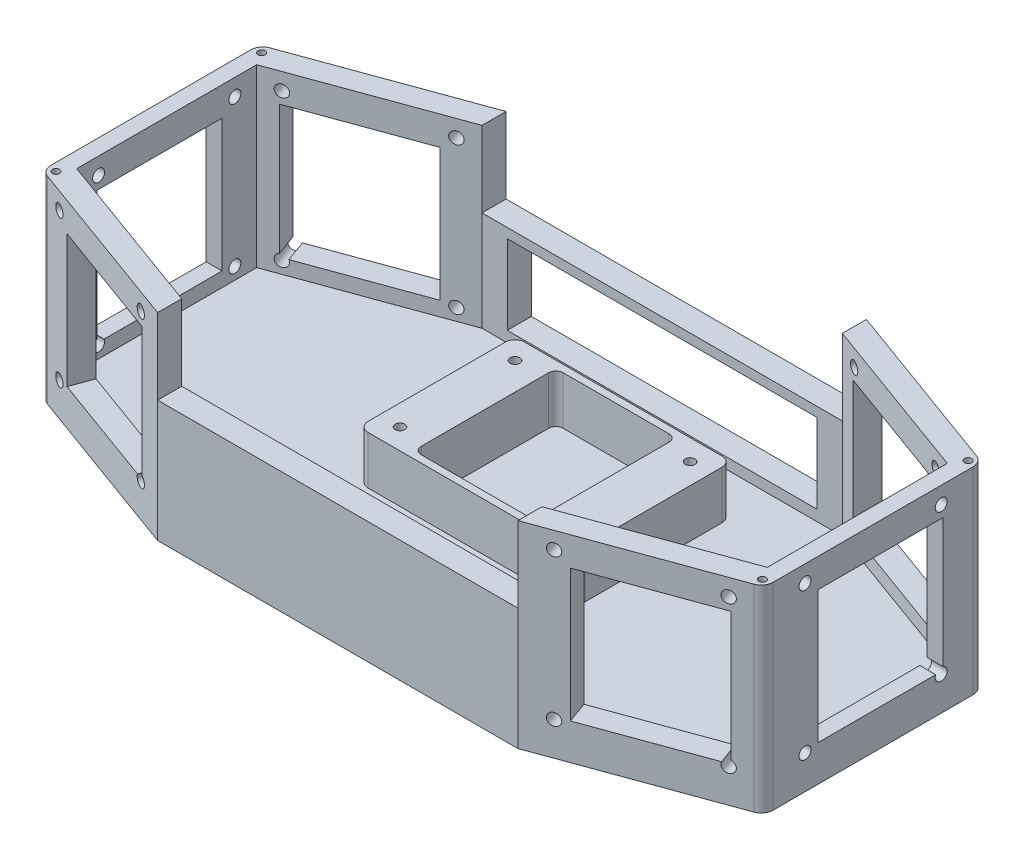
SolidWorks part; units mm, degrees
material "ABS"
ref_plane "Front Plane" through (0, 0, 0) normal (0, 0, 1) x (1, 0, 0)
ref_plane "Top Plane" through (0, 0, 0) normal (0, 1, 0) x (1, 0, 0)
ref_plane "Right Plane" through (0, 0, 0) normal (1, 0, 0) x (0, 0, -1)
sketch "Sketch1" plane through (0, 0, 0) normal (0, 1, 0) x (1, 0, 0)
  line L0 (-150, 0) -> (150, 0) construction
  line L1 (-150, 45) -> (-150, -45)
  line L2 (140.0883, -41.1583) -> (79.948, -63.0476) construction
  line L3 (-140.0883, 41.1583) -> (-142.4825, 47.7362) construction
  line L4 (-140.0883, 41.1583) -> (-79.948, 63.0476) construction
  line L5 (-150, 45) -> (-74.8246, 72.3616)
  line L6 (-79.948, 63.0476) -> (-82.3421, 69.6255) construction
  line L7 (-143, 32) -> (-143, -32) construction
  line L8 (-140.0883, -41.1583) -> (-142.4825, -47.7362) construction
  line L9 (-79.948, -63.0476) -> (-82.3421, -69.6255) construction
  line L10 (-140.0883, -41.1583) -> (-79.948, -63.0476) construction
  line L11 (-150, -45) -> (-74.8246, -72.3616)
  line L12 (0, 74.8501) -> (0, -82.9126) construction
  line L13 (79.948, -63.0476) -> (82.3421, -69.6255) construction
  line L14 (140.0883, -41.1583) -> (142.4825, -47.7362) construction
  line L15 (143, 32) -> (143, -32) construction
  line L16 (79.948, 63.0476) -> (82.3421, 69.6255) construction
  line L17 (140.0883, 41.1583) -> (79.948, 63.0476) construction
  line L18 (140.0883, 41.1583) -> (142.4825, 47.7362) construction
  line L19 (150, -45) -> (74.8246, -72.3616)
  line L20 (150, 45) -> (74.8246, 72.3616)
  line L21 (150, 45) -> (150, -45)
  line L22 (-74.8246, 72.3616) -> (74.8246, 72.3616)
  line L23 (-74.8246, -72.3616) -> (74.8246, -72.3616)
  point P0 (0, 0)
  point P3 (-150, 0)
  point P10 (-143, 0)
  point P13 (0, 0)
  point P37 (143, 0)
  dimension "D1" = 7
  dimension "D2" = 90
  dimension "D3" = 64
  dimension "D4" = 300
  dimension "D5" = 7
  dimension "D6" = 8
  dimension "D7" = 80
  dimension "D8" = 110
extrude "Boss-Extrude1" add sketch "Sketch1" along normal blind 8
sketch "Sketch2" plane through (0, 8, 0) normal (0, 1, 0) x (1, 0, 0)
  line L0 (0, 72.3616) -> (0, -72.3616) construction
  line L1 (74.8246, 72.3616) -> (-74.8246, 72.3616) construction
  line L2 (-74.8246, -72.3616) -> (74.8246, -72.3616) construction
  line L3 (-74.8246, -72.3616) -> (-74.8246, -62.3616) construction
  line L4 (-74.8246, -62.3616) -> (-64.3246, -62.3616) construction
  line L5 (-64.3246, -62.3616) -> (-64.3246, -72.3616) construction
  line L6 (-64.3246, -72.3616) -> (-74.8246, -72.3616) construction
  line L7 (64.3246, -72.3616) -> (74.8246, -72.3616) construction
  line L8 (64.3246, -62.3616) -> (64.3246, -72.3616) construction
  line L9 (74.8246, -62.3616) -> (64.3246, -62.3616) construction
  line L10 (74.8246, -72.3616) -> (74.8246, -62.3616) construction
  line L11 (-150, 0) -> (150, 0) construction
  line L12 (-150, 45) -> (-150, -45) construction
  line L13 (150, -45) -> (150, 45) construction
  line L14 (74.8246, 72.3616) -> (74.8246, 62.3616)
  line L15 (74.8246, 62.3616) -> (64.3246, 62.3616)
  line L16 (64.3246, 62.3616) -> (64.3246, 72.3616)
  line L17 (64.3246, 72.3616) -> (74.8246, 72.3616)
  line L18 (-64.3246, 72.3616) -> (-74.8246, 72.3616)
  line L19 (-64.3246, 62.3616) -> (-64.3246, 72.3616)
  line L20 (-74.8246, 62.3616) -> (-64.3246, 62.3616)
  line L21 (-74.8246, 72.3616) -> (-74.8246, 62.3616)
  dimension "D1" = 10.5
  dimension "D2" = 10
extrude "Boss-Extrude2" add sketch "Sketch2" along normal blind 37.5
sketch "Sketch4" plane through (0, 8, 0) normal (0, 1, 0) x (1, 0, 0)
  line L1 (-64.3246, 72.3616) -> (64.3246, 72.3616)
  line L2 (-64.3246, 72.3616) -> (-64.3246, 62.3616)
  line L3 (-64.3246, 62.3616) -> (64.3246, 62.3616)
  line L4 (64.3246, 72.3616) -> (64.3246, 62.3616)
extrude "Boss-Extrude4" add sketch "Sketch4" along normal blind 4.5
sketch "Sketch5" plane through (0, 8, 0) normal (0, 1, 0) x (1, 0, 0)
  line L0 (-74.8246, 62.3616) -> (-87.0406, 57.9153)
  line L1 (-74.8246, 72.3616) -> (-150, 45) construction
  line L2 (-74.8246, 72.3616) -> (-74.8246, 62.3616)
  line L3 (-74.8246, 72.3616) -> (-150, 45)
  line L4 (-87.0406, 57.9153) -> (-140.6031, 38.4202)
  line L5 (-150, 45) -> (-140.6031, 38.4202) construction
  line L6 (-74.8246, -72.3616) -> (-74.8246, -62.3616)
  line L7 (-140.6031, 38.4202) -> (-143.4222, 37.3941)
  line L8 (-150, 45) -> (-143.4222, 37.3941) construction
  line L9 (-150, 0) -> (-74.8246, 0) construction
  line L10 (-150, 45) -> (-150, -45) construction
  line L11 (-79.6003, 0) -> (86.9407, 0) construction
  line L12 (-124.0599, 0) -> (-121.8599, 0) construction
  line L13 (-74.8246, -62.3616) -> (-87.0406, -57.9153)
  line L14 (-140.6031, -38.4202) -> (-143.4222, -37.3941)
  line L15 (-87.0406, -57.9153) -> (-140.6031, -38.4202)
  line L16 (-150, -45) -> (-143.4222, -37.3941) construction
  line L17 (-74.8246, -72.3616) -> (-150, -45)
  line L18 (-143.4222, 37.3941) -> (-143.4222, -37.3941)
  line L19 (-150, 45) -> (-150, -45)
  line L20 (0, 72.1209) -> (0, -72.3616) construction
  line L21 (-74.8246, -72.3616) -> (74.8246, -72.3616) construction
  line L22 (150, -45) -> (143.4222, -37.3941) construction
  line L23 (150, 0) -> (74.8246, 0) construction
  line L24 (150, 45) -> (143.4222, 37.3941) construction
  line L25 (150, 45) -> (140.6031, 38.4202) construction
  line L26 (150, 45) -> (150, -45)
  line L27 (143.4222, 37.3941) -> (143.4222, -37.3941)
  line L28 (74.8246, -72.3616) -> (150, -45)
  line L29 (87.0406, -57.9153) -> (140.6031, -38.4202)
  line L30 (140.6031, -38.4202) -> (143.4222, -37.3941)
  line L31 (74.8246, -62.3616) -> (87.0406, -57.9153)
  line L32 (140.6031, 38.4202) -> (143.4222, 37.3941)
  line L33 (74.8246, -72.3616) -> (74.8246, -62.3616)
  line L34 (87.0406, 57.9153) -> (140.6031, 38.4202)
  line L35 (74.8246, 72.3616) -> (150, 45)
  line L36 (74.8246, 72.3616) -> (74.8246, 62.3616)
  line L37 (74.8246, 62.3616) -> (87.0406, 57.9153)
  dimension "D1" = 13
  dimension "D2" = 55
  dimension "D3" = 3
extrude "Boss-Extrude5" add sketch "Sketch5" along normal blind 10
sketch "Sketch6" plane through (0, 45.5, 0) normal (0, 1, 0) x (1, 0, 0)
  line L1 (74.8246, 72.3616) -> (-74.8246, 72.3616)
  line L2 (74.8246, 72.3616) -> (74.8246, 62.3616)
  line L3 (74.8246, 62.3616) -> (-74.8246, 62.3616)
  line L4 (-74.8246, 72.3616) -> (-74.8246, 62.3616)
extrude "Boss-Extrude6" add sketch "Sketch6" along normal blind 4
sketch "Sketch7" plane through (32.0094, 0, -87.9451) normal (0.342, 0, -0.9397) x (-0.9397, 0, -0.342)
  line L0 (-85.563, 18) -> (-85.563, 0) construction
  line L1 (-125.563, 18) -> (-45.563, 18) construction
  line L2 (-125.563, 0) -> (-45.563, 0) construction
  line L3 (-113.853, 13) -> (-85.563, 13) construction
  circle A0 centre (-113.853, 13) radius 2.5
  circle A1 centre (-57.273, 13) radius 2.5
  dimension "D1" = 56.58
  dimension "D2" = 5
  dimension "D3" = 5
extrude "Cut-Extrude1" cut sketch "Sketch7" against normal up to next
ref_plane "Plane1" through (0, 0, 0) normal (1, 0, 0) x (0, 0, -1)
mirror "Mirror1" about plane through (0, 0, 0) normal (1, 0, 0) of "Cut-Extrude1"
ref_plane "Plane2" through (0, 0, 0) normal (0, 0, -1) x (-1, 0, 0)
mirror "Mirror2" about plane through (0, 0, 0) normal (0, 0, -1) of "Cut-Extrude1", "Mirror1"
sketch "Sketch8" plane through (150, 0, 0) normal (1, 0, 0) x (0, 0, -1)
  line L0 (0, 18) -> (0, 0) construction
  line L1 (-45, 18) -> (45, 18) construction
  line L2 (-28.29, 13) -> (28.29, 13) construction
  line L3 (0, -27.775) -> (0, 27.775) construction
  circle A0 centre (-28.29, 13) radius 2.5
  circle A1 centre (28.29, 13) radius 2.5
  point P8 (0, 13)
  dimension "D1" = 56.58
  dimension "D3" = 5
  dimension "D2" = 5
extrude "Cut-Extrude2" cut sketch "Sketch8" against normal up to next
mirror "Mirror3" about plane through (0, 0, 0) normal (1, 0, 0) of "Cut-Extrude2"
sketch "Sketch9" plane through (0, 18, 0) normal (0, 1, 0) x (1, 0, 0)
  line L0 (143.4222, 23) -> (150, 23)
  line L1 (143.4222, 37.3941) -> (143.4222, -37.3941) construction
  line L2 (150, -45) -> (150, 45) construction
  line L3 (150, 23) -> (150, 45)
  line L4 (150, 45) -> (134.0252, 50.8143)
  line L5 (150, 45) -> (74.8246, 72.3616) construction
  line L6 (134.0252, 50.8143) -> (130.8113, 41.9841)
  line L7 (74.8246, 62.3616) -> (143.4222, 37.3941) construction
  line L8 (130.8113, 41.9841) -> (143.4222, 37.3941)
  line L9 (143.4222, 37.3941) -> (143.4222, 23)
  line L12 (74.8246, 72.3616) -> (90.7994, 66.5473)
  line L13 (90.7994, 66.5473) -> (87.5854, 57.717)
  line L14 (87.5854, 57.717) -> (74.8246, 62.3616)
  line L15 (74.8246, 72.3616) -> (74.8246, 62.3616) construction
  line L16 (74.8246, 62.3616) -> (74.8246, 72.3616)
  line L17 (0, -70.7131) -> (0, 92.4677) construction
  line L18 (-74.8246, 62.3616) -> (-74.8246, 72.3616)
  line L19 (-87.5854, 57.717) -> (-74.8246, 62.3616)
  line L20 (-90.7994, 66.5473) -> (-87.5854, 57.717)
  line L21 (-74.8246, 72.3616) -> (-90.7994, 66.5473)
  line L22 (-143.4222, 37.3941) -> (-143.4222, 23)
  line L23 (-130.8113, 41.9841) -> (-143.4222, 37.3941)
  line L24 (-134.0252, 50.8143) -> (-130.8113, 41.9841)
  line L25 (-150, 45) -> (-134.0252, 50.8143)
  line L26 (-150, 23) -> (-150, 45)
  line L27 (-143.4222, 23) -> (-150, 23)
  line L28 (150, 0) -> (-150, 0) construction
  line L29 (-150, 45) -> (-150, -45) construction
  line L30 (143.4222, -37.3941) -> (143.4222, -23)
  line L31 (130.8113, -41.9841) -> (143.4222, -37.3941)
  line L32 (134.0252, -50.8143) -> (130.8113, -41.9841)
  line L33 (150, -45) -> (134.0252, -50.8143)
  line L34 (150, -23) -> (150, -45)
  line L35 (143.4222, -23) -> (150, -23)
  line L36 (-143.4222, -23) -> (-150, -23)
  line L37 (-150, -23) -> (-150, -45)
  line L38 (-150, -45) -> (-134.0252, -50.8143)
  line L39 (-134.0252, -50.8143) -> (-130.8113, -41.9841)
  line L40 (-130.8113, -41.9841) -> (-143.4222, -37.3941)
  line L41 (-143.4222, -37.3941) -> (-143.4222, -23)
  line L42 (-74.8246, -72.3616) -> (-90.7994, -66.5473)
  line L43 (-90.7994, -66.5473) -> (-87.5854, -57.717)
  line L44 (-87.5854, -57.717) -> (-74.8246, -62.3616)
  line L45 (-74.8246, -62.3616) -> (-74.8246, -72.3616)
  line L46 (74.8246, -62.3616) -> (74.8246, -72.3616)
  line L47 (87.5854, -57.717) -> (74.8246, -62.3616)
  line L48 (90.7994, -66.5473) -> (87.5854, -57.717)
  line L49 (74.8246, -72.3616) -> (90.7994, -66.5473)
  dimension "D1" = 22
  dimension "D2" = 17
  dimension "D3" = 17
extrude "Boss-Extrude8" add sketch "Sketch9" along normal blind 63
sketch "Sketch10" plane through (32.0094, 0, -87.9451) normal (0.342, 0, -0.9397) x (-0.9397, 0, -0.342)
  line L0 (-85.563, 0) -> (-85.563, 86.9159) construction
  line L1 (-125.563, 0) -> (-45.563, 0) construction
  line L2 (-113.853, 13) -> (-113.853, 74) construction
  circle A0 centre (-113.853, 74) radius 2.5
  circle A1 centre (-113.853, 13) radius 2.5 construction
  circle A2 centre (-57.273, 74) radius 2.5
  dimension "D1" = 61
extrude "Cut-Extrude3" cut sketch "Sketch10" against normal up to next
mirror "Mirror4" about plane through (0, 0, 0) normal (1, 0, 0) of "Cut-Extrude3"
mirror "Mirror5" about plane through (0, 0, 0) normal (0, 0, -1) of "Cut-Extrude3", "Mirror4"
sketch "Sketch11" plane through (150, 0, 0) normal (1, 0, 0) x (0, 0, -1)
  line L0 (-28.29, 13) -> (-28.29, 74) construction
  line L1 (0, 18) -> (0, 79.1024) construction
  line L2 (-23, 18) -> (23, 18) construction
  circle A0 centre (-28.29, 74) radius 2.5
  circle A1 centre (-28.29, 13) radius 2.5 construction
  circle A2 centre (28.29, 74) radius 2.5
  dimension "D1" = 61
extrude "Cut-Extrude4" cut sketch "Sketch11" against normal up to next
mirror "Mirror6" about plane through (0, 0, 0) normal (1, 0, 0) of "Cut-Extrude4"
sketch "Sketch12" plane through (0, 81, 0) normal (0, 1, 0) x (1, 0, 0)
  line L0 (130.8113, 41.9841) -> (87.5854, 57.717)
  line L1 (87.5854, 57.717) -> (90.7994, 66.5473)
  line L2 (90.7994, 66.5473) -> (134.0252, 50.8143)
  line L3 (134.0252, 50.8143) -> (130.8113, 41.9841)
  line L4 (0, 103.9036) -> (0, -116.4859) construction
  line L5 (143.4222, 23) -> (150, 23)
  line L6 (143.4222, 23) -> (143.4222, -23)
  line L7 (143.4222, -23) -> (150, -23)
  line L8 (150, 23) -> (150, -23)
  line L9 (150, 0) -> (-150, 0) construction
  line L10 (-150, 23) -> (-150, -23) construction
  line L11 (134.0252, -50.8143) -> (130.8113, -41.9841)
  line L12 (90.7994, -66.5473) -> (134.0252, -50.8143)
  line L13 (87.5854, -57.717) -> (90.7994, -66.5473)
  line L14 (130.8113, -41.9841) -> (87.5854, -57.717)
  line L15 (-130.8113, -41.9841) -> (-87.5854, -57.717)
  line L16 (-87.5854, -57.717) -> (-90.7994, -66.5473)
  line L17 (-90.7994, -66.5473) -> (-134.0252, -50.8143)
  line L18 (-134.0252, -50.8143) -> (-130.8113, -41.9841)
  line L19 (-150, 23) -> (-150, -23)
  line L20 (-143.4222, -23) -> (-150, -23)
  line L21 (-143.4222, 23) -> (-143.4222, -23)
  line L22 (-143.4222, 23) -> (-150, 23)
  line L23 (-134.0252, 50.8143) -> (-130.8113, 41.9841)
  line L24 (-90.7994, 66.5473) -> (-134.0252, 50.8143)
  line L25 (-87.5854, 57.717) -> (-90.7994, 66.5473)
  line L26 (-130.8113, 41.9841) -> (-87.5854, 57.717)
extrude "Boss-Extrude9" add sketch "Sketch12" against normal blind 12
sketch "Sketch13" plane through (0, 8, 0) normal (0, 1, 0) x (1, 0, 0)
  line L0 (0, 62.3616) -> (0, -72.3616) construction
  line L1 (-41, 46.2316) -> (-29, 46.2316)
  line L2 (-45, 42.2316) -> (-45, -14.7684)
  line L3 (-41, -18.7684) -> (-29, -18.7684)
  line L4 (45, 42.2316) -> (45, -14.7684)
  line L5 (-74.8246, 62.3616) -> (74.8246, 62.3616) construction
  line L6 (-74.8246, -72.3616) -> (74.8246, -72.3616) construction
  line L7 (-25, 40.2316) -> (-25, -12.7684)
  line L8 (25, 40.2316) -> (25, -12.7684)
  line L9 (29, 46.2316) -> (41, 46.2316)
  line L10 (29, -18.7684) -> (41, -18.7684)
  line L11 (-25, 46.2316) -> (25, 46.2316) construction
  line L12 (-25, -18.7684) -> (25, -18.7684) construction
  line L13 (-29, 46.2316) -> (29, 46.2316)
  line L14 (-22, 43.2316) -> (22, 43.2316)
  line L15 (-22, -15.7684) -> (22, -15.7684)
  line L16 (-29, -18.7684) -> (29, -18.7684)
  arc A0 (-45, -14.7684) -> (-41, -18.7684) centre (-41, -14.7684) ccw
  arc A1 (41, -18.7684) -> (45, -14.7684) centre (41, -14.7684) ccw
  arc A2 (41, 46.2316) -> (45, 42.2316) centre (41, 42.2316) cw
  arc A3 (-41, 46.2316) -> (-45, 42.2316) centre (-41, 42.2316) ccw
  arc A4 (-25, -12.7684) -> (-22, -15.7684) centre (-22, -12.7684) ccw
  arc A5 (25, -12.7684) -> (22, -15.7684) centre (22, -12.7684) cw
  arc A6 (25, 40.2316) -> (22, 43.2316) centre (22, 40.2316) ccw
  arc A7 (-25, 40.2316) -> (-22, 43.2316) centre (-22, 40.2316) cw
  point P10 (0, 46.2316)
  point P15 (45, -18.7684)
  point P18 (45, 46.2316)
  point P21 (-45, 46.2316)
  dimension "D4" = 4
  dimension "D7" = 3
  dimension "D9" = 3
  dimension "D1" = 65
  dimension "D2" = 90
  dimension "D3" = 16.13
  dimension "D5" = 20
  dimension "D6" = 25
  dimension "D8" = 3
extrude "Boss-Extrude10" add sketch "Sketch13" along normal blind 20
sketch "Sketch14" plane through (0, 28, 0) normal (0, 1, 0) x (1, 0, 0)
  line L0 (-45, 42.2316) -> (-45, -14.7684) construction
  line L1 (-36.37, 37.6066) -> (-36.37, -10.1434) construction
  line L2 (-45, 13.7316) -> (-25, 13.7316) construction
  line L3 (-25, -12.7684) -> (-25, 40.2316) construction
  circle A0 centre (-36.37, 37.6066) radius 2
  circle A1 centre (-36.37, -10.1434) radius 2
  point P10 (-36.37, 13.7316)
  dimension "D1" = 4
  dimension "D2" = 47.75
  dimension "D3" = 8.63
extrude "Cut-Extrude5" cut sketch "Sketch14" against normal blind 10
mirror "Mirror7" about plane through (0, 0, 0) normal (1, 0, 0) of "Cut-Extrude5"
sketch "Sketch15" plane through (0, 8, 0) normal (0, 1, 0) x (1, 0, 0)
  line L1 (-74.8246, -72.3616) -> (74.8246, -72.3616)
  line L2 (-74.8246, -72.3616) -> (-74.8246, -62.3616)
  line L3 (-74.8246, -62.3616) -> (74.8246, -62.3616)
  line L4 (74.8246, -72.3616) -> (74.8246, -62.3616)
extrude "Boss-Extrude11" add sketch "Sketch15" along normal blind 41.5
sketch "Sketch16" plane through (0, 0, -72.3616) normal (0, 0, -1) x (-1, 0, 0)
  line L0 (-74.8246, 81) -> (-47.5, 81)
  line L1 (0, 0) -> (0, 104.0722) construction
  line L2 (0, 45.1) -> (0, -45.1) construction
  line L3 (74.8246, 81) -> (47.5, 81)
  line L4 (-74.8246, 49.5) -> (74.8246, 49.5) construction
  line L5 (-74.8246, 81) -> (-74.8246, 49.5)
  line L6 (-74.8246, 49.5) -> (74.8246, 49.5)
  line L7 (74.8246, 49.5) -> (74.8246, 81)
  arc A0 (-47.5, 81) -> (47.5, 81) centre (0, 101.0635) ccw
  dimension "D1" = 95
sketch "Sketch17" plane through (0, 81, 0) normal (0, 1, 0) x (1, 0, 0)
  line L0 (150, -45) -> (123.1193, -26.178) construction
  line L1 (150, 0) -> (-150, 0) construction
  line L2 (150, -45) -> (150, 45) construction
  line L3 (-150, 45) -> (-150, -45) construction
  line L4 (0, 76.5626) -> (0, -108.8084) construction
  circle A0 centre (146.7234, -42.7057) radius 1.5
  circle A1 centre (146.7234, 42.7057) radius 1.5
  circle A2 centre (-146.7234, 42.7057) radius 1.5
  circle A3 centre (-146.7234, -42.7057) radius 1.5
  dimension "D2" = 3
  dimension "D1" = 55
  dimension "D3" = 4
extrude "Cut-Extrude6" cut sketch "Sketch17" against normal blind 10
sketch "Esquisse1" plane through (0, 8, 0) normal (0, 1, 0) x (1, 0, 0)
  line L0 (-132, 21) -> (-132, -21)
  line L1 (-132, -21) -> (-120, -21)
  line L2 (-120, -21) -> (-120, 21)
  line L3 (-120, 21) -> (-132, 21)
  line L4 (0, 62.3616) -> (0, -62.3616) construction
  line L5 (-74.8246, 62.3616) -> (74.8246, 62.3616) construction
  line L6 (74.8246, -62.3616) -> (-74.8246, -62.3616) construction
  line L7 (120, 21) -> (132, 21)
  line L8 (120, -21) -> (120, 21)
  line L9 (132, -21) -> (120, -21)
  line L10 (132, 21) -> (132, -21)
  line L11 (-150, 0) -> (150, 0) construction
  line L12 (-150, 45) -> (-150, -45) construction
  line L13 (150, -45) -> (150, 45) construction
  line L14 (-74.8246, 62.3616) -> (-74.8246, -62.3616) construction
  line L15 (-95.8246, 31) -> (-53.8246, 31)
  line L16 (-95.8246, 31) -> (-95.8246, 19)
  line L17 (-95.8246, 19) -> (-53.8246, 19)
  line L18 (-53.8246, 31) -> (-53.8246, 19)
  line L19 (-95.8246, 31) -> (-53.8246, 19) construction
  line L20 (-95.8246, 19) -> (-53.8246, 31) construction
  line L21 (-95.8246, -19) -> (-53.8246, -31) construction
  line L22 (-95.8246, -31) -> (-53.8246, -19) construction
  line L23 (-53.8246, -31) -> (-53.8246, -19)
  line L24 (-95.8246, -19) -> (-53.8246, -19)
  line L25 (-95.8246, -31) -> (-95.8246, -19)
  line L26 (-95.8246, -31) -> (-53.8246, -31)
  line L27 (95.8246, -31) -> (53.8246, -19) construction
  line L28 (95.8246, -19) -> (53.8246, -31) construction
  line L29 (95.8246, 19) -> (53.8246, 31) construction
  line L30 (95.8246, 31) -> (53.8246, 19) construction
  line L31 (95.8246, -31) -> (53.8246, -31)
  line L32 (95.8246, -31) -> (95.8246, -19)
  line L33 (95.8246, -19) -> (53.8246, -19)
  line L34 (53.8246, -31) -> (53.8246, -19)
  line L35 (53.8246, 31) -> (53.8246, 19)
  line L36 (95.8246, 19) -> (53.8246, 19)
  line L37 (95.8246, 31) -> (95.8246, 19)
  line L38 (95.8246, 31) -> (53.8246, 31)
  point P20 (-120, 0)
  point P21 (-74.8246, 25)
  point P34 (-74.8246, -25)
  point P43 (74.8246, -25)
  point P44 (74.8246, 25)
  dimension "D1" = 12
  dimension "D2" = 42
  dimension "D3" = 120
  dimension "D4" = 25
extrude "Enlèv. mat.-Extru.1" cut sketch "Esquisse1" against normal blind 6 from offset 2 offset against normal yes
sketch "Esquisse2" plane through (0, 0, 0) normal (0, -1, 0) x (1, 0, 0)
  line L8 (-150, -45) -> (-74.8246, -72.3616)
  line L9 (-74.8246, -72.3616) -> (74.8246, -72.3616)
  line L10 (74.8246, -72.3616) -> (150, -45)
  line L11 (150, -45) -> (150, 45)
  line L12 (150, 45) -> (74.8246, 72.3616)
  line L13 (74.8246, 72.3616) -> (-74.8246, 72.3616)
  line L14 (-74.8246, 72.3616) -> (-150, 45)
  line L15 (-150, 45) -> (-150, -45)
  line L16 (-150, -45) -> (-74.8246, -72.3616)
  line L17 (-74.8246, -72.3616) -> (74.8246, -72.3616)
  line L18 (74.8246, -72.3616) -> (150, -45)
  line L19 (150, -45) -> (150, 45)
  line L20 (150, 45) -> (74.8246, 72.3616)
  line L21 (74.8246, 72.3616) -> (-74.8246, 72.3616)
  line L22 (-74.8246, 72.3616) -> (-150, 45)
  line L23 (-150, 45) -> (-150, -45)
  dimension "D1" = 0
extrude "Boss.-Extru.1" add sketch "Esquisse2" along normal blind 1
fillet "Congé1" radius 5 4 edges at (150, 40, 45) (150, 40, -45) (-150, 40, -45) (-150, 40, 45)
sketch "Esquisse3" plane through (-32.0094, 0, 87.9451) normal (-0.342, 0, 0.9397) x (0.9397, 0, 0.342)
  line L0 (-62.563, 69) -> (-62.563, 18) construction
  line L1 (-108.563, 69) -> (-56.563, 69)
  line L2 (-108.563, 69) -> (-108.563, 14)
  line L3 (-108.563, 14) -> (-56.563, 14)
  line L4 (-56.563, 69) -> (-56.563, 14)
  line L5 (-108.563, 18) -> (-62.563, 18) construction
  circle A0 centre (-57.273, 13) radius 2.5
  circle A2 centre (-57.273, 13) radius 2.5 construction
  line M5 (-62.563, 69) -> (-62.563, 18)
  line M6 (-62.563, 18) -> (-108.563, 18)
  circle M9 centre (-57.273, 13) radius 2.5
  dimension "D1" = 6
  dimension "D2" = 4
extrude "Enlèv. mat.-Extru.2" cut sketch "Esquisse3" against normal blind 10 contours L4 L1 L2 L3 M5 M6 M9
sketch "Esquisse5" plane through (-150, 0, 0) normal (-1, 0, 0) x (0, 0, 1)
  line L0 (23, 69) -> (23, 18) construction
  line L1 (-23, 69) -> (29, 69)
  line L2 (-23, 69) -> (-23, 14)
  line L3 (-23, 14) -> (29, 14)
  line L4 (29, 69) -> (29, 14)
  line L7 (-23, 18) -> (23, 18) construction
  dimension "D1" = 6
  dimension "D2" = 4
extrude "Enlèv. mat.-Extru.3" cut sketch "Esquisse5" against normal blind 10
sketch "Esquisse6" plane through (-32.0094, 0, -87.9451) normal (-0.342, 0, -0.9397) x (-0.9397, 0, 0.342)
  line L0 (108.563, 69) -> (108.563, 18) construction
  line L1 (62.563, 69) -> (114.563, 69)
  line L2 (62.563, 69) -> (62.563, 14)
  line L3 (62.563, 14) -> (114.563, 14)
  line L4 (114.563, 69) -> (114.563, 14)
  line L5 (62.563, 18) -> (108.563, 18) construction
  dimension "D1" = 6
  dimension "D2" = 4
extrude "Enlèv. mat.-Extru.4" cut sketch "Esquisse6" against normal blind 10
sketch "Esquisse7" plane through (32.0094, 0, -87.9451) normal (0.342, 0, -0.9397) x (-0.9397, 0, -0.342)
  line L0 (-62.563, 69) -> (-62.563, 18) construction
  line L1 (-108.563, 69) -> (-56.563, 69)
  line L2 (-108.563, 69) -> (-108.563, 14)
  line L3 (-108.563, 14) -> (-56.563, 14)
  line L4 (-56.563, 69) -> (-56.563, 14)
  line L5 (-108.563, 18) -> (-62.563, 18) construction
  dimension "D1" = 6
  dimension "D2" = 4
extrude "Enlèv. mat.-Extru.5" cut sketch "Esquisse7" against normal blind 10
sketch "Esquisse8" plane through (150, 0, 0) normal (1, 0, 0) x (0, 0, -1)
  line L0 (23, 69) -> (23, 18) construction
  line L1 (-23, 69) -> (29, 69)
  line L2 (-23, 69) -> (-23, 14)
  line L3 (-23, 14) -> (29, 14)
  line L4 (29, 69) -> (29, 14)
  line L5 (-23, 18) -> (23, 18) construction
  dimension "D1" = 6
  dimension "D2" = 4
extrude "Enlèv. mat.-Extru.6" cut sketch "Esquisse8" against normal blind 10
sketch "Esquisse9" plane through (32.0094, 0, 87.9451) normal (0.342, 0, 0.9397) x (0.9397, 0, -0.342)
  line L0 (108.563, 69) -> (108.563, 18) construction
  line L1 (62.563, 69) -> (114.563, 69)
  line L2 (62.563, 69) -> (62.563, 14)
  line L3 (62.563, 14) -> (114.563, 14)
  line L4 (114.563, 69) -> (114.563, 14)
  line L5 (62.563, 18) -> (108.563, 18) construction
  dimension "D1" = 6
  dimension "D2" = 4
extrude "Enlèv. mat.-Extru.7" cut sketch "Esquisse9" against normal blind 10
